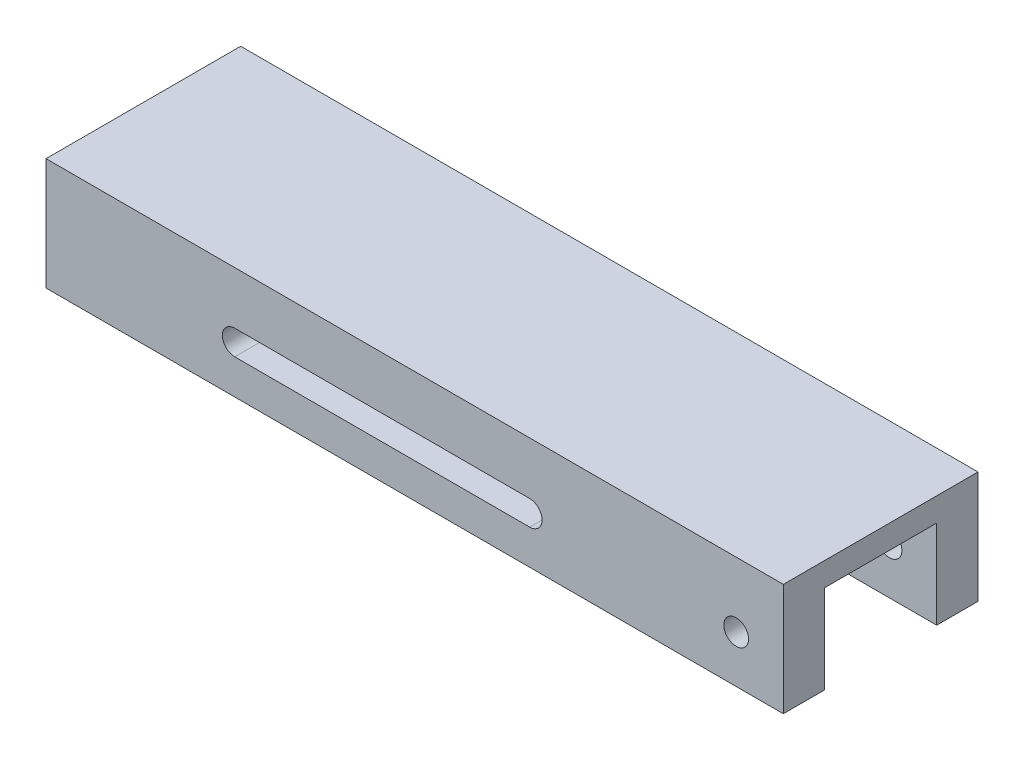
SolidWorks part; units mm, degrees
ref_plane "Front Plane" through (0, 0, 0) normal (0, 0, 1) x (1, 0, 0)
ref_plane "Top Plane" through (0, 0, 0) normal (0, 1, 0) x (1, 0, 0)
ref_plane "Right Plane" through (0, 0, 0) normal (1, 0, 0) x (0, 0, -1)
sketch "Sketch1" plane through (0, 0, 0) normal (0, 1, 0) x (1, 0, 0)
  line L0 (125, 26) -> (125, 33)
  line L1 (0, 0) -> (125, 0)
  line L2 (0, 0) -> (0, 33)
  line L3 (0, 33) -> (125, 33)
  line L4 (125, 0) -> (125, 7)
  line L5 (125, 26) -> (7, 26)
  line L7 (125, 7) -> (7, 7)
  line L8 (7, 26) -> (7, 7)
  dimension "D1" = 33
  dimension "D2" = 19
  dimension "D3" = 7
  dimension "D4" = 7
  dimension "D5" = 125
extrude "Boss-Extrude1" add sketch "Sketch1" along normal blind 15
sketch "Sketch2" plane through (0, 15, 0) normal (0, 1, 0) x (1, 0, 0)
  line L1 (0, 33) -> (125, 33)
  line L2 (0, 33) -> (0, 0)
  line L3 (0, 0) -> (125, 0)
  line L4 (125, 33) -> (125, 0)
sketch "Sketch3" plane through (0, 0, 0) normal (0, 0, 1) x (1, 0, 0)
  line L0 (117, 8) -> (32, 8) construction
  line L2 (41.1426, 8) -> (29.9, 8) construction
  line L3 (82, 8) -> (32, 8) construction
  line L4 (82, 5.9) -> (32, 5.9)
  line L5 (82, 10.1) -> (32, 10.1)
  line L6 (125, 15) -> (125, 0) construction
  line L10 (0, 0) -> (125, 0) construction
  circle A0 centre (117, 8) radius 2.1
  circle A1 centre (117, 8) radius 4.1 construction
  arc A2 (82, 5.9) -> (82, 10.1) centre (82, 8) ccw
  arc A3 (32, 10.1) -> (32, 5.9) centre (32, 8) ccw
  point P10 (57, 8)
  dimension "D1" = 4.2
  dimension "D2" = 2
  dimension "D4" = 2.1
  dimension "D5" = 35
  dimension "D3" = 8
  dimension "D6" = 85
  dimension "D7" = 8
extrude "Cut-Extrude2" cut sketch "Sketch3" against normal through all
extrude "Boss-Extrude4" add sketch "Sketch2" along normal blind 4
sketch "Sketch6" plane through (7, 0, 0) normal (1, 0, 0) x (0, 0, -1)
  line L0 (16.5, 0) -> (16.5, 15) construction
  line L1 (7, 0) -> (26, 0) construction
  line L2 (7, 15) -> (26, 15) construction
  circle A0 centre (16.5, 8) radius 3.575
  dimension "D1" = 7.15
  dimension "D2" = 7
sketch "Sketch8" plane through (0, 15, 0) normal (0, -1, 0) x (1, 0, 0)
  line L0 (125, -7) -> (7, -7) construction
  line L1 (90, -7) -> (97, -7)
  line L2 (90, -7) -> (90, -26)
  line L3 (90, -26) -> (97, -26)
  line L4 (97, -7) -> (97, -26)
  line L5 (7, -26) -> (125, -26) construction
  line L6 (125, -7) -> (125, -26) construction
  dimension "D1" = 7
  dimension "D2" = 28
extrude "Boss-Extrude5" add sketch "Sketch8" along normal blind 15
extrude "Cut-Extrude4" cut sketch "Sketch6" along normal up to surface and the other way through all up to face at (97, 7.5, -16.5)
